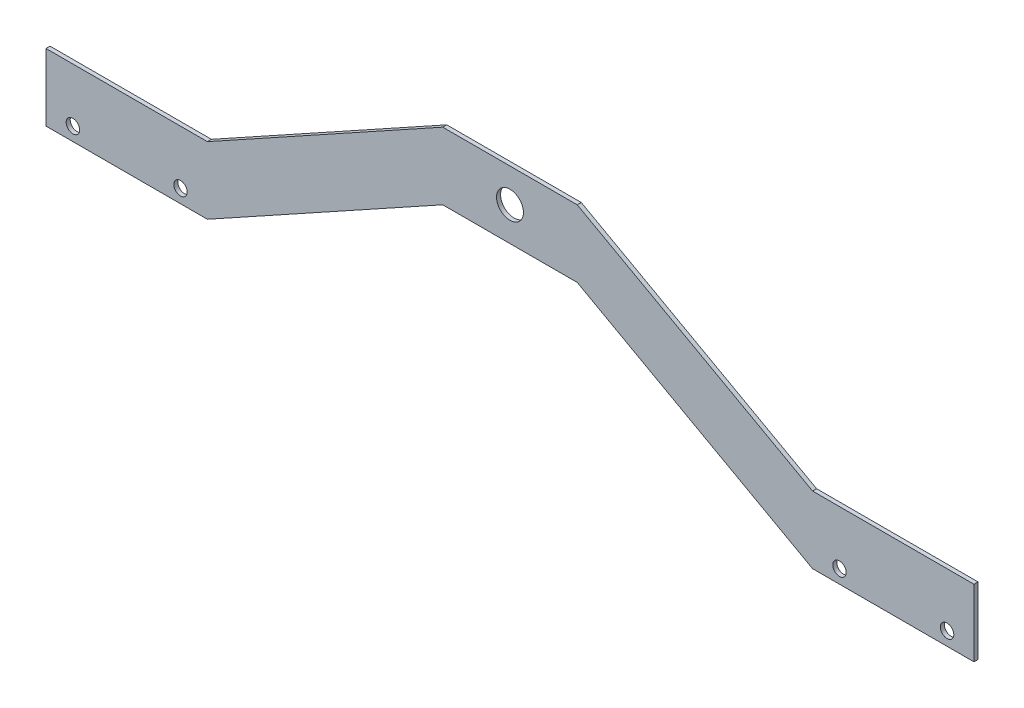
SolidWorks part; units mm, degrees
ref_plane "Front Plane" through (0, 0, 0) normal (0, 0, 1) x (1, 0, 0)
ref_plane "Top Plane" through (0, 0, 0) normal (0, 1, 0) x (1, 0, 0)
ref_plane "Right Plane" through (0, 0, 0) normal (1, 0, 0) x (0, 0, -1)
sketch "Sketch1" plane through (0, 0, 0) normal (0, 0, 1) x (1, 0, 0)
  line L0 (62.3684, 57.479) -> (-112.6316, 154.3036)
  line L1 (62.3684, 57.479) -> (182.3684, 57.479)
  line L2 (62.3684, 57.479) -> (62.3684, 7.479)
  line L3 (62.3684, 7.479) -> (182.3684, 7.479)
  line L4 (182.3684, 57.479) -> (182.3684, 7.479)
  line L5 (62.3684, 57.479) -> (182.3684, 7.479) construction
  line L6 (62.3684, 7.479) -> (182.3684, 57.479) construction
  line L7 (-112.6316, 154.3036) -> (-212.6316, 154.3036)
  line L8 (-212.6316, 154.3036) -> (-387.6316, 57.479)
  line L9 (62.3684, 7.479) -> (-112.6316, 104.3036)
  line L10 (-112.6316, 104.3036) -> (-212.6316, 104.3036)
  line L11 (-212.6316, 104.3036) -> (-387.6316, 7.479)
  line L12 (-387.6316, 7.479) -> (-387.6316, 57.479)
  line L13 (-387.6316, 57.479) -> (-507.6316, 57.479)
  line L14 (-507.6316, 57.479) -> (-507.6316, 7.479)
  line L15 (-507.6316, 7.479) -> (-387.6316, 7.479)
  point P0 (122.3684, 32.479)
  dimension "D1" = 50
  dimension "D2" = 120
  dimension "D3" = 200
  dimension "D4" = 100
  dimension "D5" = 200
  dimension "D6" = 450
  dimension "D7" = 120
  dimension "D8" = 50
extrude "Boss-Extrude1" add sketch "Sketch1" along normal blind 3 contours L4 L1 L2 L3 | L12 L11 L10 L9 L2 L0 L7 L8 | L14 L15 L12 L13
sketch "Sketch2" plane through (0, 0, 3) normal (0, 0, 1) x (1, 0, 0)
  line L0 (-507.6316, 7.479) -> (-387.6316, 7.479) construction
  line L1 (-507.6316, 57.479) -> (-507.6316, 7.479) construction
  line L2 (-112.6316, 154.3036) -> (-212.6316, 154.3036) construction
  circle A0 centre (-487.6316, 17.479) radius 5
  circle A1 centre (-407.6316, 17.479) radius 5
  circle A2 centre (82.3684, 17.479) radius 5
  circle A3 centre (162.3684, 17.479) radius 5
  circle A4 centre (-162.6316, 129.3036) radius 10
  dimension "D1" = 10
  dimension "D2" = 10
  dimension "D7" = 20
  dimension "D3" = 10
  dimension "D4" = 20
  dimension "D5" = 10
  dimension "D6" = 20
  dimension "D8" = 25
  dimension "D9" = 50
extrude "Cut-Extrude1" cut sketch "Sketch2" against normal through all contours A4 | A1 | A0 | A3 | A2
